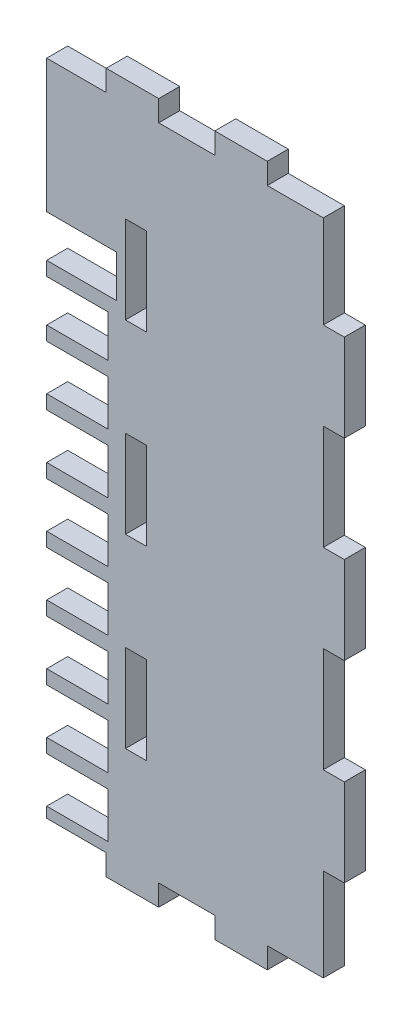
SolidWorks part; units mm, degrees
ref_plane "Plan de face" through (0, 0, 0) normal (0, 0, 1) x (1, 0, 0)
ref_plane "Plan de dessus" through (0, 0, 0) normal (0, 1, 0) x (1, 0, 0)
ref_plane "Plan de droite" through (0, 0, 0) normal (1, 0, 0) x (0, 0, -1)
sketch "Esquisse1" plane through (0, 0, 0) normal (0, 0, 1) x (1, 0, 0)
  line L1 (39.5, -94) -> (-39.5, -94)
  line L2 (39.5, -94) -> (39.5, 94)
  line L3 (39.5, 94) -> (-39.5, 94)
  line L4 (-39.5, -94) -> (-39.5, 94)
  line L5 (39.5, -94) -> (-39.5, 94) construction
  line L6 (39.5, 94) -> (-39.5, -94) construction
  point P0 (0, 0)
  dimension "D1" = 188
  dimension "D2" = 79
extrude "Boss.-Extru.1" add sketch "Esquisse1" along normal blind 6
sketch "Esquisse2" plane through (0, 0, 6) normal (0, 0, 1) x (1, 0, 0)
  line L0 (-39.5, 94) -> (-39.5, -94) construction
  line L1 (-39.5, 56) -> (-19.5, 56)
  line L2 (-39.5, 56) -> (-39.5, 44)
  line L3 (-19.5, 44) -> (-39.5, 44)
  line L4 (-19.5, 56) -> (-19.5, 44)
  line L5 (39.5, 94) -> (-39.5, 94) construction
  line L15 (-39.5, 28) -> (-22, 28)
  line L16 (-39.5, 11) -> (-22, 11)
  line L17 (-39.5, -6) -> (-22, -6)
  line L18 (-39.5, -23) -> (-22, -23)
  line L19 (-39.5, -40) -> (-22, -40)
  line L20 (-39.5, -57) -> (-22, -57)
  line L21 (-39.5, -74) -> (-22, -74)
  line L22 (-39.5, -91) -> (-22, -91)
  line L25 (-22, 28) -> (-22, 40)
  line L26 (-22, 40) -> (-39.5, 40)
  line L27 (-39.5, 28) -> (-39.5, 40)
  line L29 (-22, 11) -> (-22, 24)
  line L30 (-22, 24) -> (-39.5, 24)
  line L31 (-39.5, 11) -> (-39.5, 24)
  line L33 (-22, -6) -> (-22, 7)
  line L34 (-22, 7) -> (-39.5, 7)
  line L35 (-39.5, -6) -> (-39.5, 7)
  line L37 (-22, -23) -> (-22, -10)
  line L38 (-22, -10) -> (-39.5, -10)
  line L39 (-39.5, -23) -> (-39.5, -10)
  line L41 (-22, -40) -> (-22, -27)
  line L42 (-22, -27) -> (-39.5, -27)
  line L43 (-39.5, -40) -> (-39.5, -27)
  line L45 (-22, -57) -> (-22, -44)
  line L46 (-22, -44) -> (-39.5, -44)
  line L47 (-39.5, -57) -> (-39.5, -44)
  line L49 (-22, -74) -> (-22, -61)
  line L50 (-22, -61) -> (-39.5, -61)
  line L51 (-39.5, -74) -> (-39.5, -61)
  line L53 (-22, -91) -> (-22, -78)
  line L54 (-22, -78) -> (-39.5, -78)
  line L55 (-39.5, -91) -> (-39.5, -78)
  dimension "D1" = 12
  dimension "D2" = 20
  dimension "D3" = 38
  dimension "D6" = 12
  dimension "D7" = 13
  dimension "D8" = 13
  dimension "D9" = 13
  dimension "D10" = 13
  dimension "D11" = 13
  dimension "D12" = 13
  dimension "D13" = 13
  dimension "D4" = 4
  dimension "D5" = 4
  dimension "D14" = 4
  dimension "D15" = 4
  dimension "D16" = 4
  dimension "D17" = 4
  dimension "D18" = 4
  dimension "D19" = 4
  dimension "D20" = 17.5
extrude "Enlèv. mat.-Extru.1" cut sketch "Esquisse2" against normal blind 10
sketch "Esquisse3" plane through (39.5, 0, 0) normal (1, 0, 0) x (0, 0, -1)
  line L0 (0, -94) -> (0, 94) construction
  line L1 (0, 67.5) -> (-6, 67.5)
  line L2 (0, 67.5) -> (0, 42.5)
  line L3 (0, 42.5) -> (-6, 42.5)
  line L4 (-6, 67.5) -> (-6, 42.5)
  line L5 (-6, -94) -> (-6, 94) construction
  line L7 (0, 12.5) -> (-6, 12.5)
  line L8 (0, 12.5) -> (0, -12.5)
  line L9 (0, -12.5) -> (-6, -12.5)
  line L10 (-6, 12.5) -> (-6, -12.5)
  line L11 (0, -42.5) -> (-6, -42.5)
  line L12 (0, -42.5) -> (0, -67.5)
  line L13 (0, -67.5) -> (-6, -67.5)
  line L14 (-6, -42.5) -> (-6, -67.5)
  dimension "D1" = 25
  dimension "D2" = 25
  dimension "D3" = 25
  dimension "D4" = 26.5
  dimension "D5" = 30
  dimension "D6" = 30
extrude "Boss.-Extru.2" add sketch "Esquisse3" along normal blind 6
sketch "Esquisse4" plane through (0, 94, 0) normal (0, 1, 0) x (1, 0, 0)
  line L0 (39.5, 0) -> (-39.5, 0) construction
  line L1 (-22.5, 0) -> (-7.5, 0)
  line L2 (-22.5, 0) -> (-22.5, -6)
  line L3 (-22.5, -6) -> (-7.5, -6)
  line L4 (-7.5, 0) -> (-7.5, -6)
  line L5 (39.5, -6) -> (-39.5, -6) construction
  line L7 (8.5, 0) -> (23.5, 0)
  line L8 (8.5, 0) -> (8.5, -6)
  line L9 (8.5, -6) -> (23.5, -6)
  line L10 (23.5, 0) -> (23.5, -6)
  dimension "D1" = 15
  dimension "D2" = 15
  dimension "D3" = 16
  dimension "D4" = 16
extrude "Boss.-Extru.3" add sketch "Esquisse4" along normal blind 6
sketch "Esquisse5" plane through (0, -94, 0) normal (0, -1, 0) x (1, 0, 0)
  line L0 (-39.5, 6) -> (39.5, 6) construction
  line L1 (23.5, 6) -> (8.5, 6)
  line L2 (23.5, 6) -> (23.5, 0)
  line L3 (23.5, 0) -> (8.5, 0)
  line L4 (8.5, 6) -> (8.5, 0)
  line L5 (-39.5, 0) -> (39.5, 0) construction
  line L6 (39.5, 6) -> (39.5, 0) construction
  line L7 (-7.5, 6) -> (-22.5, 6)
  line L8 (-7.5, 6) -> (-7.5, 0)
  line L9 (-7.5, 0) -> (-22.5, 0)
  line L10 (-22.5, 6) -> (-22.5, 0)
  dimension "D1" = 15
  dimension "D2" = 15
  dimension "D3" = 16
  dimension "D4" = 16
extrude "Boss.-Extru.4" add sketch "Esquisse5" along normal blind 6
sketch "Esquisse6" plane through (0, 0, 0) normal (0, 0, -1) x (-1, 0, 0)
  line L0 (22, -91) -> (22, -78) construction
  line L1 (11, -65.5) -> (17, -65.5)
  line L2 (11, -65.5) -> (11, -40.5)
  line L3 (11, -40.5) -> (17, -40.5)
  line L4 (17, -65.5) -> (17, -40.5)
  line L7 (11.015, -12.5) -> (17, -12.5)
  line L8 (11.015, -12.5) -> (11.015, 12.5)
  line L9 (11.015, 12.5) -> (17, 12.5)
  line L10 (17, -12.5) -> (17, 12.5)
  line L11 (11, 40.5) -> (17, 40.5)
  line L12 (11, 40.5) -> (11, 65.5)
  line L13 (11, 65.5) -> (17, 65.5)
  line L14 (17, 40.5) -> (17, 65.5)
  point P4 (22, -84.5)
  dimension "D1" = 6
  dimension "D2" = 5
  dimension "D3" = 25
  dimension "D4" = 28.5
  dimension "D5" = 25
  dimension "D6" = 28
  dimension "D7" = 25
  dimension "D8" = 28
extrude "Enlèv. mat.-Extru.2" cut sketch "Esquisse6" against normal blind 10
